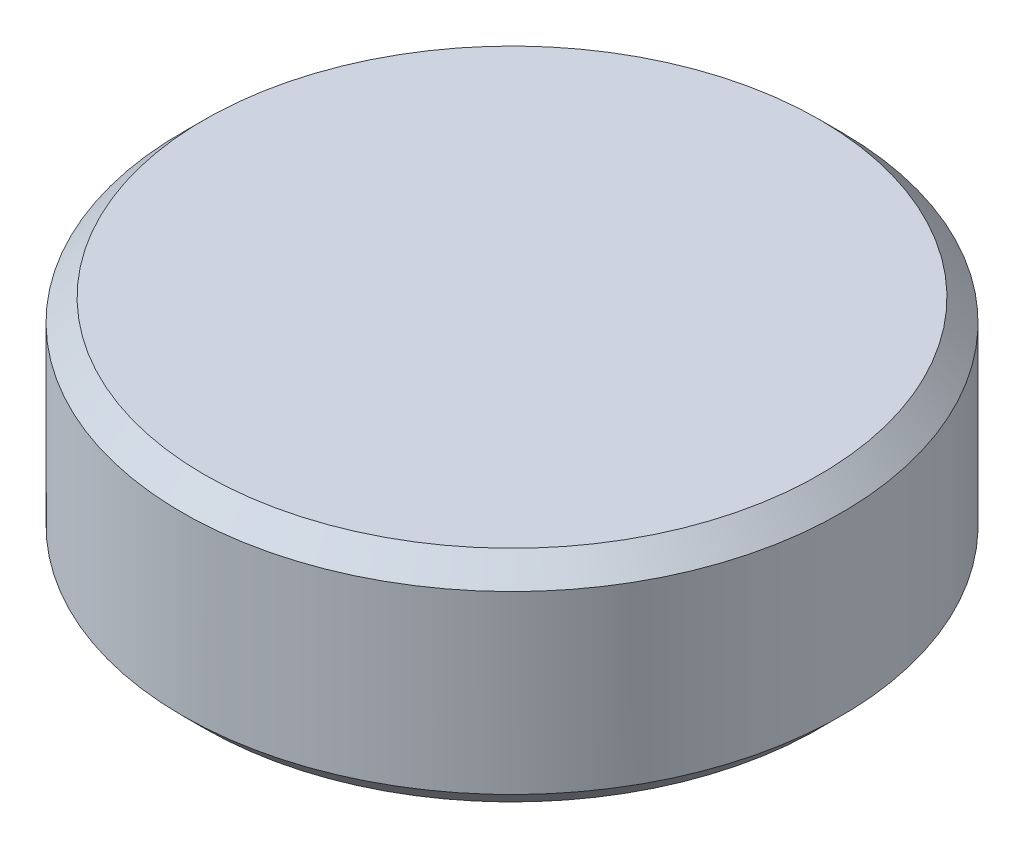
SolidWorks part; units mm, degrees
material "AISI 1020"
ref_plane "Front Plane" through (0, 0, 0) normal (0, 0, 1) x (1, 0, 0)
ref_plane "Top Plane" through (0, 0, 0) normal (0, 1, 0) x (1, 0, 0)
ref_plane "Right Plane" through (0, 0, 0) normal (1, 0, 0) x (0, 0, -1)
sketch "Sketch1" plane through (0, 0, 0) normal (0, 1, 0) x (1, 0, 0)
  circle A0 centre (0, 0) radius 3
  dimension "D1" = 6
extrude "Boss-Extrude1" add sketch "Sketch1" along normal blind 2
chamfer "Chamfer1" distance 0.2 angle 45 2 edges at (0, 0, 3) (0, 2, 3)
